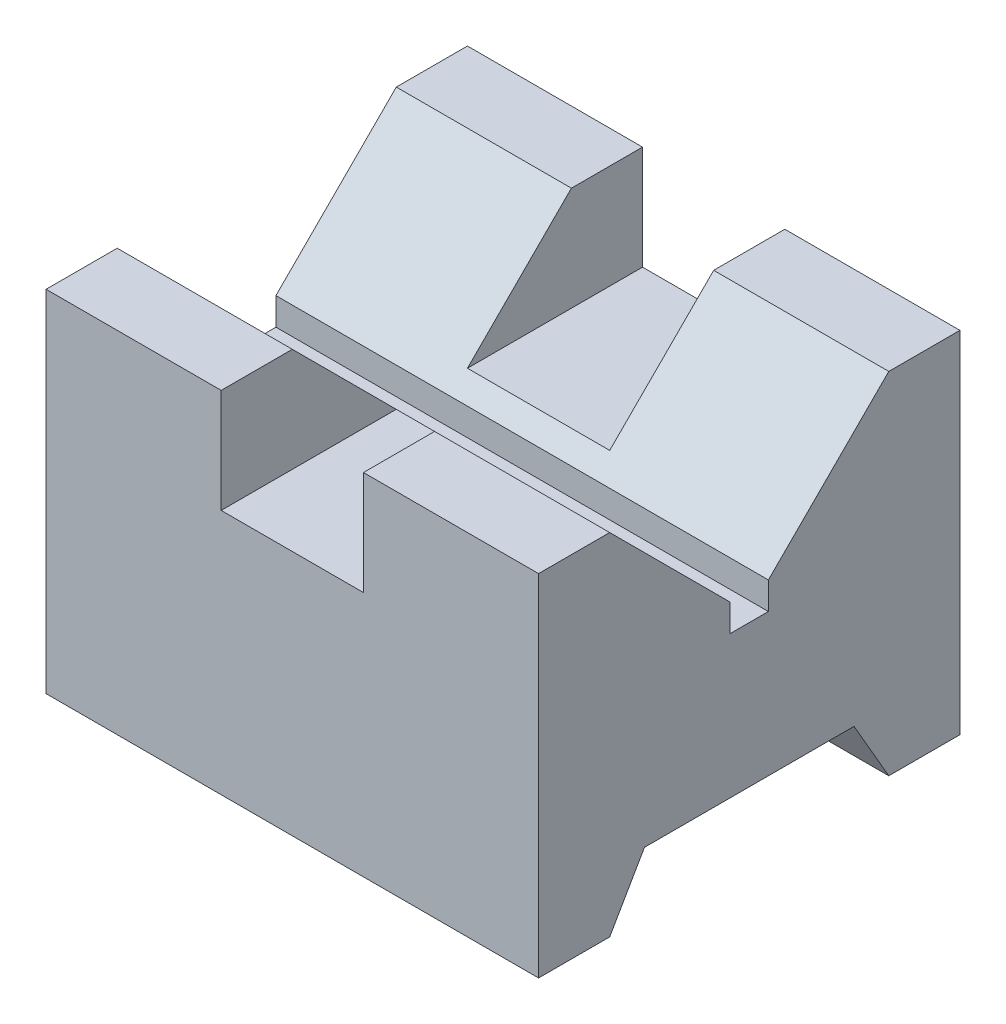
SolidWorks part; units mm, degrees
ref_plane "Ön Düzlem" through (0, 0, 0) normal (0, 0, 1) x (1, 0, 0)
ref_plane "Üst Düzlem" through (0, 0, 0) normal (0, 1, 0) x (1, 0, 0)
ref_plane "Sağ Düzlem" through (0, 0, 0) normal (1, 0, 0) x (0, 0, -1)
sketch "Çizim6" plane through (0, 0, 0) normal (0, 0, 1) x (1, 0, 0)
  line L1 (-450, 320) -> (450, 320)
  line L2 (-450, 320) -> (-450, -320)
  line L3 (-450, -320) -> (450, -320)
  line L4 (450, 320) -> (450, -320)
  line L5 (-450, 320) -> (450, -320) construction
  line L6 (-450, -320) -> (450, 320) construction
  point P0 (0, 0)
  dimension "D1" = 900
  dimension "D2" = 640
extrude "Yükseklik-Ekstrüzyon3" add sketch "Çizim6" along normal blind 770
sketch "Çizim7" plane through (0, 0, 770) normal (0, 0, 1) x (1, 0, 0)
  line L0 (-130, 320) -> (130, 320)
  line L1 (450, 320) -> (-450, 320) construction
  line L2 (-130, 320) -> (-130, 130)
  line L3 (-130, 130) -> (130, 130)
  line L4 (130, 130) -> (130, 320)
  dimension "D1" = 260
  dimension "D2" = 190
extrude "Kes-Ekstrüzyon4" cut sketch "Çizim7" against normal blind 770
sketch "Çizim8" plane through (450, 0, 0) normal (1, 0, 0) x (0, 0, -1)
  line L0 (-385, 320) -> (-385, -320) construction
  line L1 (-350, 50) -> (-350, 100)
  line L2 (-350, 100) -> (-130, 320)
  line L3 (-770, 320) -> (0, 320) construction
  line L4 (-770, -320) -> (0, -320) construction
  line L5 (-640, 320) -> (-420, 100)
  line L6 (-420, 100) -> (-420, 50)
  line L7 (-420, 50) -> (-350, 50)
  line L8 (-130, 320) -> (-640, 320)
  dimension "D1" = 130
  dimension "D2" = 270
  dimension "D3" = 70
  dimension "D4" = 90
extrude "Kes-Ekstrüzyon6" cut sketch "Çizim8" against normal up to surface (900 mm away) up to face at (-450, 0, 385)
sketch "Çizim13" plane through (450, 0, 0) normal (1, 0, 0) x (0, 0, -1)
  line L0 (-640, -320) -> (-576.4915, -210)
  line L1 (-770, -320) -> (0, -320) construction
  line L2 (-576.4915, -210) -> (-193.5085, -210)
  line L3 (-193.5085, -210) -> (-130, -320)
  line L4 (-385, -320) -> (-385, 306.273) construction
  line L5 (-640, -320) -> (-130, -320)
  dimension "D1" = 110
  dimension "D2" = 130
  dimension "D3" = 60
extrude "Kes-Ekstrüzyon7" cut sketch "Çizim13" against normal up to surface (900 mm away) up to face at (-450, 94, 385)
